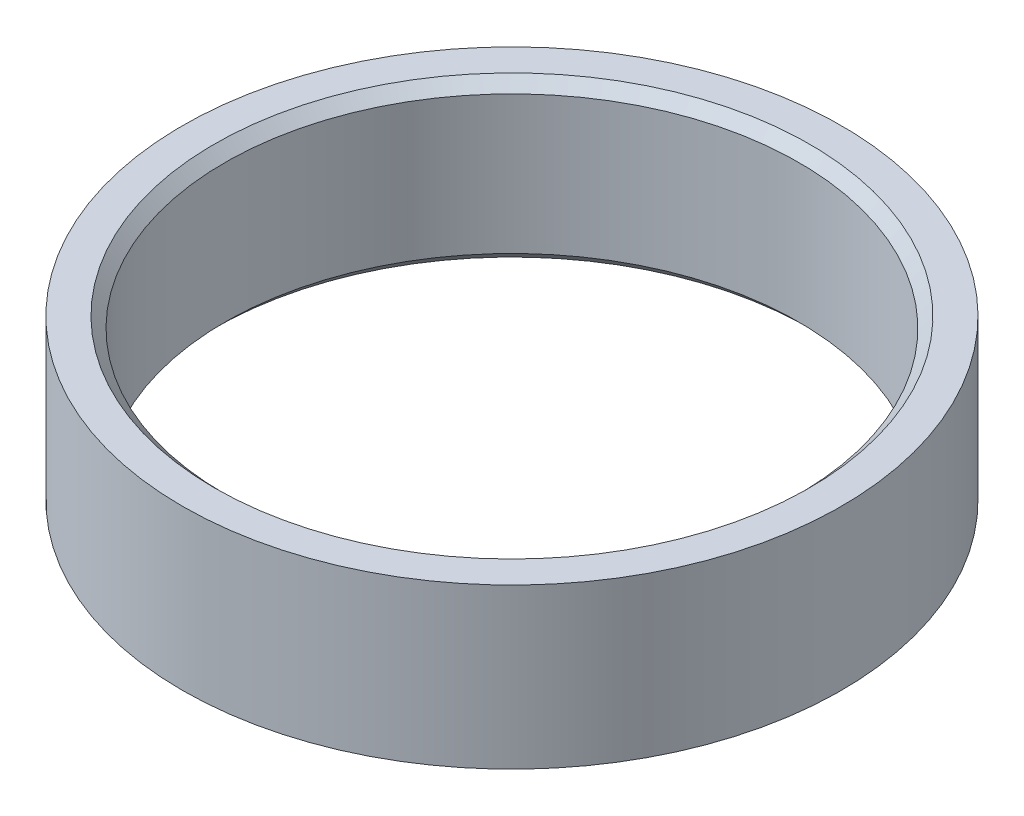
SolidWorks part; units mm, degrees
material "6061-T6 铝合金"
ref_plane "前视基准面" through (0, 0, 0) normal (0, 0, 1) x (1, 0, 0)
ref_plane "上视基准面" through (0, 0, 0) normal (0, 1, 0) x (1, 0, 0)
ref_plane "右视基准面" through (0, 0, 0) normal (1, 0, 0) x (0, 0, -1)
sketch "草图1" plane through (0, 0, 0) normal (0, 1, 0) x (1, 0, 0)
  circle A0 centre (0, 0) radius 15.5
  circle A1 centre (0, 0) radius 13.5
  dimension "D1" = 31
  dimension "D2" = 27
extrude "凸台-拉伸1" add sketch "草图1" along normal blind 7.5
chamfer "倒角1" distance 0.5 angle 45 2 edges at (0, 0, 13.5) (0, 7.5, 13.5)
